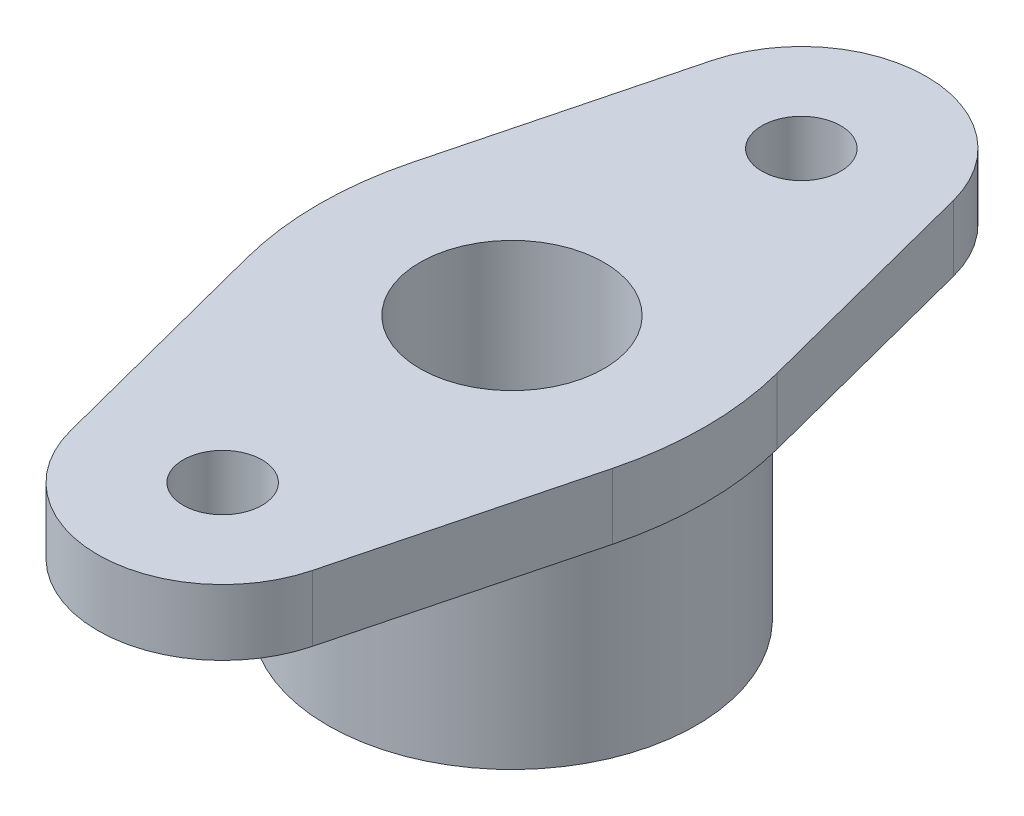
SolidWorks part; units mm, degrees
ref_plane "Front Plane" through (0, 0, 0) normal (0, 0, 1) x (1, 0, 0)
ref_plane "Top Plane" through (0, 0, 0) normal (0, 1, 0) x (1, 0, 0)
ref_plane "Right Plane" through (0, 0, 0) normal (1, 0, 0) x (0, 0, -1)
sketch "Sketch1" plane through (0, 0, 0) normal (0, 1, 0) x (1, 0, 0)
  line L0 (-31, 0) -> (-18.3952, -48.7557)
  line L1 (-31, 0) -> (-18.3952, 48.7557)
  line L2 (0, 44) -> (0, 20.6327) construction
  line L3 (31, 0) -> (18.3952, 48.7557)
  line L4 (31, 0) -> (-31, 0) construction
  line L5 (31, 0) -> (18.3952, -48.7557)
  circle A0 centre (0, 44) radius 6
  circle A1 centre (0, 44) radius 19
  circle A2 centre (0, 0) radius 14
  circle A3 centre (0, -44) radius 6
  circle A4 centre (0, -44) radius 19
  point P3 (0, 0)
  dimension "D1" = 12
  dimension "D2" = 38
  dimension "D4" = 28
  dimension "D3" = 88
  dimension "D5" = 62
extrude "Boss-Extrude1" add sketch "Sketch1" along normal blind 10 contours L0 A4 L5 L3 A1 L1 A2 | A4 A3 | A1 A0
fillet "Fillet1" radius 50 2 edges at (-31, 5, 0) (31, 5, 0)
sketch "Sketch2" plane through (0, 0, 0) normal (0, 0, 1) x (1, 0, 0)
  line L0 (0, 0) -> (0, -21.2252) construction
  line L1 (14, 0) -> (28, 0)
  line L2 (28, 0) -> (28, -30)
  line L3 (28, -30) -> (14, -21.9171)
  line L4 (14, -21.9171) -> (14, 0)
  point P7 (0, 0)
  dimension "D1" = 60
  dimension "D2" = 30
  dimension "D3" = 28
revolve "Revolve1" add sketch "Sketch2" angle 360 about L0
